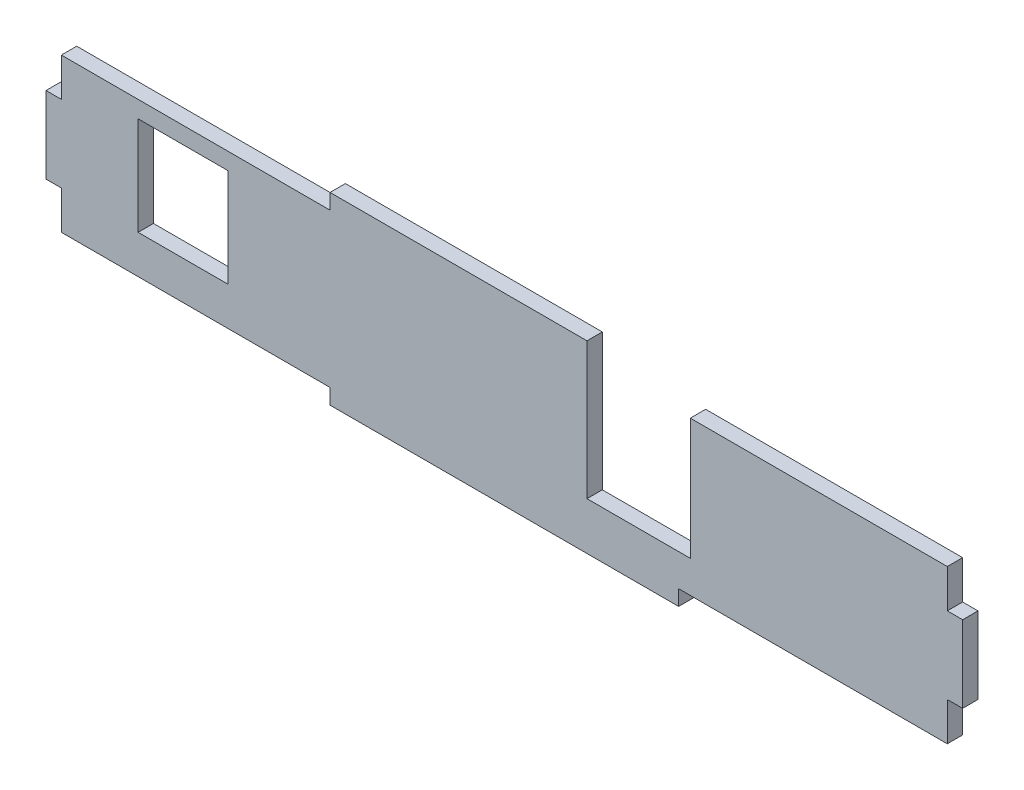
SolidWorks part; units mm, degrees
ref_plane "Front Plane" through (0, 0, 0) normal (0, 0, 1) x (1, 0, 0)
ref_plane "Top Plane" through (0, 0, 0) normal (0, 1, 0) x (1, 0, 0)
ref_plane "Right Plane" through (0, 0, 0) normal (1, 0, 0) x (0, 0, -1)
sketch "Sketch1" plane through (0, 0, 0) normal (0, 0, 1) x (1, 0, 0)
  line L14 (0, 0) -> (35, 0)
  line L15 (35, 0) -> (35, -2.0005)
  line L16 (35, -2.0005) -> (80.41, -2.0005)
  line L17 (80.41, -2.0005) -> (80.41, 0)
  line L18 (80.41, 0) -> (115.41, 0)
  line L19 (0, 0) -> (0, 5)
  line L20 (0, 5) -> (-2, 5)
  line L21 (-2, 5) -> (-2, 15)
  line L22 (-2, 15) -> (0, 15)
  line L23 (0, 15) -> (0, 20)
  line L24 (115.41, 0) -> (115.41, 5)
  line L25 (115.41, 5) -> (117.41, 5)
  line L26 (117.41, 5) -> (117.41, 15)
  line L27 (117.41, 15) -> (115.41, 15)
  line L28 (115.41, 15) -> (115.41, 20.0036)
  line L31 (35, 22) -> (35, 20)
  line L32 (81.9297, 20.0036) -> (115.41, 20.0036)
  line L34 (0, 20) -> (35, 20)
  line L35 (68.4731, 4.1892) -> (81.9297, 4.1892)
  line L36 (10, 5) -> (21.6952, 5)
  line L37 (10, 5) -> (10, 17.8079)
  line L38 (10, 17.8079) -> (21.6952, 17.8079)
  line L39 (21.6952, 5) -> (21.6952, 17.8079)
  line L40 (68.4731, 4.1892) -> (68.4731, 15.5986)
  line L44 (35, 22) -> (68.4731, 22)
  line L45 (-4, 19.9511) -> (119.41, 19.9511) construction
  line L46 (68.4731, 19.9511) -> (68.4731, 22)
  line L48 (68.4731, 19.9511) -> (68.4731, 15.5986)
  line L50 (81.9297, 20.0036) -> (81.9297, 4.1892)
  dimension "D1" = 10
  dimension "D2" = 115.41
  dimension "D3" = 5
extrude "Boss-Extrude1" add sketch "Sketch1" along normal blind 2
